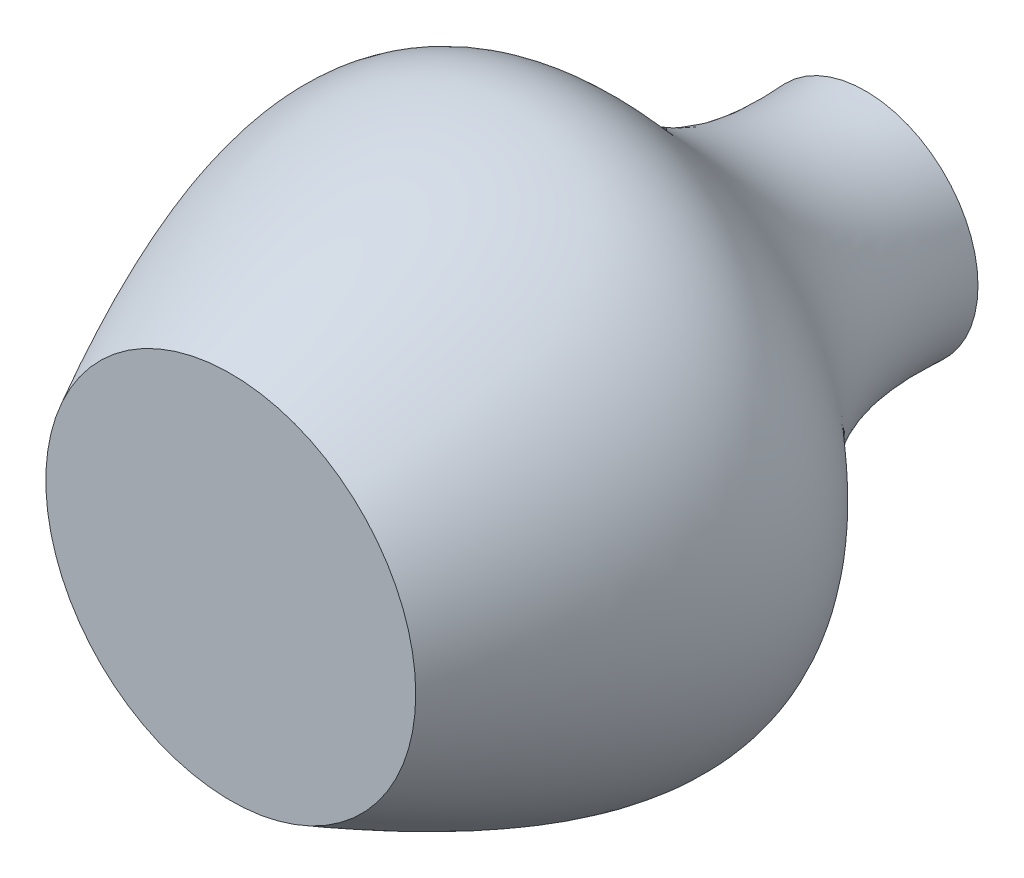
SolidWorks part; units mm, degrees
ref_plane "Front Plane" through (0, 0, 0) normal (0, 0, 1) x (1, 0, 0)
ref_plane "Top Plane" through (0, 0, 0) normal (0, 1, 0) x (1, 0, 0)
ref_plane "Right Plane" through (0, 0, 0) normal (1, 0, 0) x (0, 0, -1)
sketch "Sketch2" plane through (0, 0, 0) normal (0, 1, 0) x (1, 0, 0)
  line L0 (0, 0) -> (-20, 0) construction
  line L1 (-20, 0) -> (-10, 32.9906) construction
  line L2 (-10, 32.9906) -> (0, 0) construction
  line L3 (-20, 0) -> (-48.2819, 52.9777) construction
  line L4 (-48.2819, 52.9777) -> (-10, 32.9906) construction
  line L5 (-10, 32.9906) -> (-12.1608, 68.6302) construction
  line L6 (0, 0) -> (0, 68.6302)
  line L7 (0, 68.6302) -> (-12.1608, 68.6302)
  line L8 (0, 0) -> (-20, 0)
  line L9 (0, 0) -> (0, 113.4549) construction
  spline S0 degree 3 poles (-20, 0) (-48.2819, 52.9777) (-10, 32.9906) (-12.1608, 68.6302) knots 0 0 0 0 1 1 1 1
revolve "Revolve1" add sketch "Sketch2" angle 360 about L9
